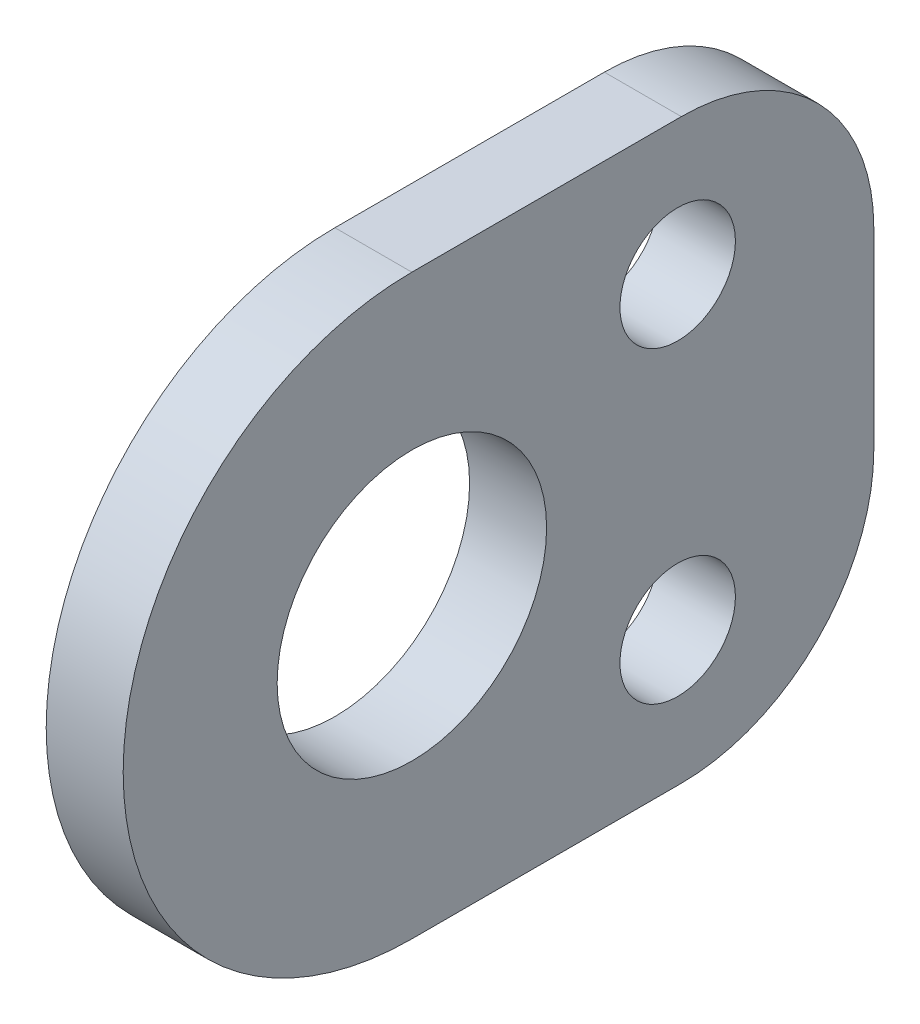
SolidWorks part; units mm, degrees
material "Plain Carbon Steel"
ref_plane "Front Plane" through (0, 0, 0) normal (0, 0, 1) x (1, 0, 0)
ref_plane "Top Plane" through (0, 0, 0) normal (0, 1, 0) x (1, 0, 0)
ref_plane "Right Plane" through (0, 0, 0) normal (1, 0, 0) x (0, 0, -1)
sketch "Sketch1" plane through (0, 0, 0) normal (1, 0, 0) x (0, 0, -1)
  line L0 (6.9051, 4) -> (6.9051, -4) construction
  line L1 (0, 7.5) -> (12, 7.5)
  line L2 (12, 7.5) -> (12, -7.5)
  line L3 (12, -7.5) -> (0, -7.5)
  arc A1 (6.9051, -4) -> (6.9051, 4) centre (0, 0) ccw construction
  circle A2 centre (6.9051, -4) radius 1.5
  circle A3 centre (6.9051, 4) radius 1.5
  circle A5 centre (0, 0) radius 3.5
  arc A7 (0, 7.5) -> (0, -7.5) centre (0, 0) ccw
  point P21 (12, 0)
  dimension "D1" = 15
  dimension "D2" = 7.98
  dimension "D4" = 3
  dimension "D5" = 12
  dimension "D6" = 7
  dimension "D3" = 8
extrude "Boss-Extrude1" add sketch "Sketch1" along normal blind 2
fillet "Fillet1" radius 5 2 edges at (1, 7.5, -12) (1, -7.5, -12)
